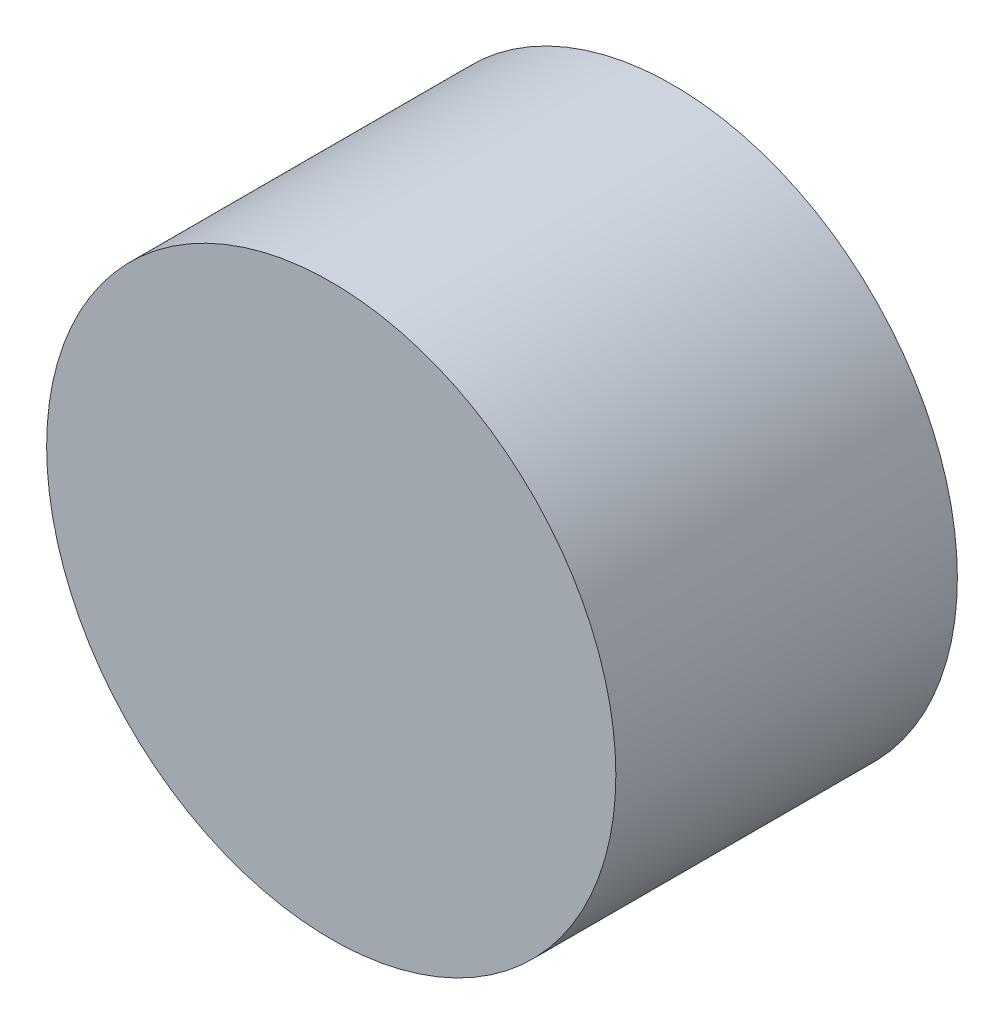
SolidWorks part; units mm, degrees
ref_plane "Front Plane" through (0, 0, 0) normal (0, 0, 1) x (1, 0, 0)
ref_plane "Top Plane" through (0, 0, 0) normal (0, 1, 0) x (1, 0, 0)
ref_plane "Right Plane" through (0, 0, 0) normal (1, 0, 0) x (0, 0, -1)
sketch "Sketch1" plane through (0, 0, 0) normal (0, 0, 1) x (1, 0, 0)
  circle A0 centre (0, 0) radius 25
  dimension "D1" = 50
extrude "Boss-Extrude1" add sketch "Sketch1" along normal blind 30
ref_plane "Plane6" through (0, 20, 0) normal (0, 1, 0) x (1, 0, 0)
ref_plane "Plane7" through (0, 60, 0) normal (0, 1, 0) x (1, 0, 0)
sketch "Sketch14" plane through (0, 20, 0) normal (0, 1, 0) x (1, 0, 0)
  line L0 (26.5952, -35.0881) -> (-32.2364, 2.8442)
  line L1 (0, -36.2788) -> (0, 4.3254) construction
  dimension "D1" = 70
sketch "Sketch17" plane through (0, 60, 0) normal (0, 1, 0) x (1, 0, 0)
  line L0 (0, 18.1178) -> (0, -51.8822)
  point P3 (0, -47.0047)
  point P4 (0, -51.8822)
  dimension "D1" = 70
